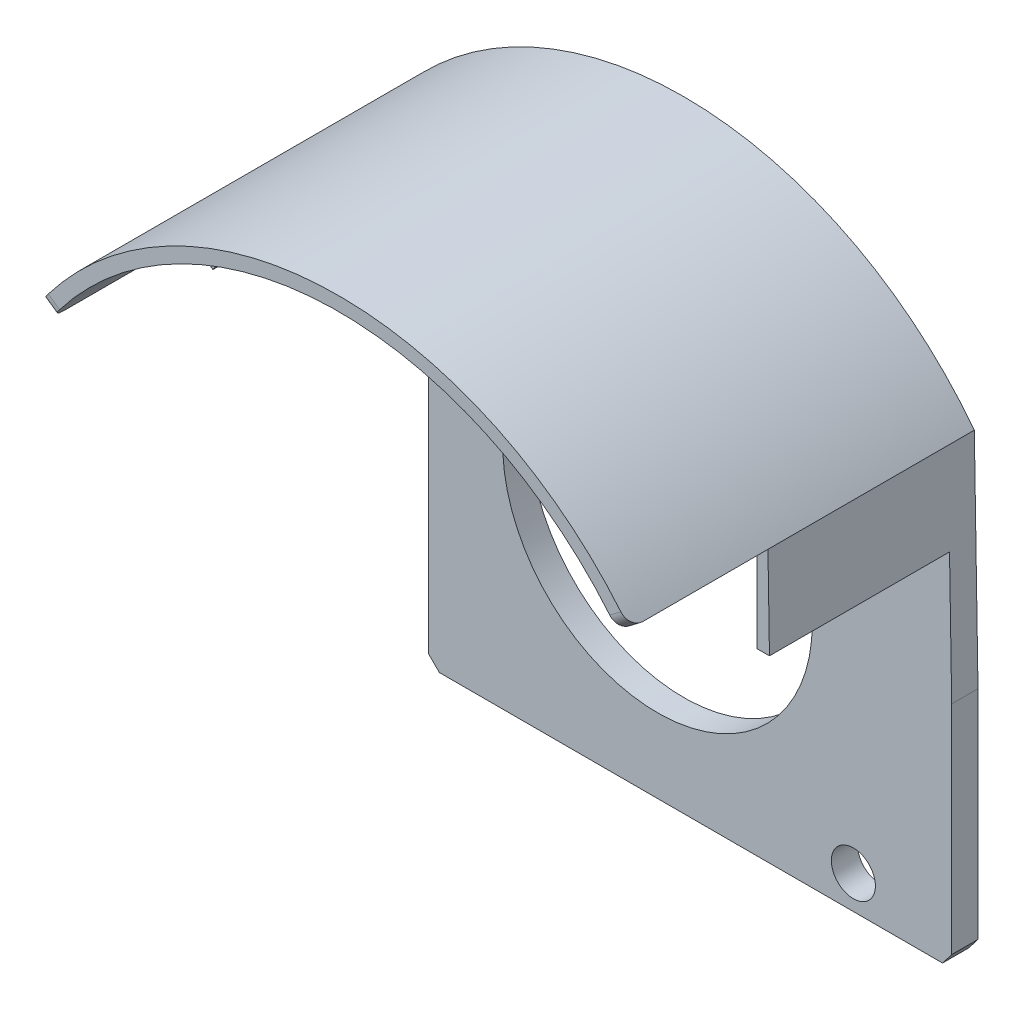
SolidWorks part; units mm, degrees
ref_plane "Front Plane" through (0, 0, 0) normal (0, 0, 1) x (1, 0, 0)
ref_plane "Top Plane" through (0, 0, 0) normal (0, 1, 0) x (1, 0, 0)
ref_plane "Right Plane" through (0, 0, 0) normal (1, 0, 0) x (0, 0, -1)
sketch "Sketch1" plane through (0, 0, 0) normal (0, 0, 1) x (1, 0, 0)
  line L1 (-21, 14.8277) -> (-21, -20)
  line L2 (-21, -20) -> (-20, -21)
  line L3 (-20, -21) -> (26.1367, -21)
  line L8 (28.2448, 0) -> (26.9748, 0) construction
  line L9 (28.2448, -18.7357) -> (28.2448, 18.7357) construction
  line L10 (26.9748, 0) -> (26.6379, 20.3604)
  line L12 (26.9748, 0) -> (26.9748, -19.912)
  line L13 (26.1367, -21) -> (26.9748, -19.912)
  line L14 (-21, 14.8277) -> (-27.3887, 19.3387)
  circle A0 centre (-17.9605, 17.9605) radius 2.0193
  circle A1 centre (17.9605, -17.9605) radius 2.0193
  circle A2 centre (0, 0) radius 14.195
  arc A6 (-27.3887, 19.3387) -> (26.6379, 20.3604) centre (0, 0) cw
extrude "Boss-Extrude1" add sketch "Sketch1" along normal blind 2.413
sketch "Sketch2" plane through (0, 0, 2.413) normal (0, 0, 1) x (1, 0, 0)
  line L0 (-26.3626, 18.5902) -> (-27.4004, 19.3221)
  line L1 (25.6289, 19.5892) -> (26.6379, 20.3604)
  arc A0 (26.6379, 20.3604) -> (-27.4004, 19.3221) centre (0, 0) ccw
  arc A1 (25.6289, 19.5892) -> (-26.3626, 18.5902) centre (0, 0) ccw
  dimension "D1" = 1.27
extrude "Boss-Extrude2" add sketch "Sketch2" along normal blind 29.21
sketch "Sketch3" plane through (0, 0, 2.413) normal (0, 0, 1) x (1, 0, 0)
  line L0 (25.6289, 19.5892) -> (25.6289, 11.9692)
  line L1 (25.6289, 11.9692) -> (26.7768, 11.9692)
  line L2 (26.9748, 0) -> (26.6379, 20.3604) construction
  line L3 (26.7768, 11.9692) -> (26.6379, 20.3604)
  line L4 (25.6289, 19.5892) -> (26.6379, 20.3604) construction
  line L5 (26.6379, 20.3604) -> (25.6289, 19.5892)
  line L7 (-25.5985, 19.629) -> (-23.5528, 18.1234)
  line L8 (-23.5528, 18.1234) -> (-24.2564, 17.127)
  line L9 (-26.3513, 18.6061) -> (-21, 14.8277) construction
  line L10 (-24.2564, 17.127) -> (-26.3513, 18.6061)
  line L12 (0.025, 32.258) -> (0.025, 25.908)
  line L13 (0.025, 25.908) -> (-1.245, 25.908)
  line L14 (-1.245, 25.908) -> (-1.245, 32.234)
  arc A0 (25.6289, 19.5892) -> (-26.3513, 18.6061) centre (0, 0) ccw construction
  arc A1 (0.025, 32.258) -> (-1.245, 32.234) centre (0, 0) ccw
  arc A2 (-25.5985, 19.629) -> (-26.3513, 18.6061) centre (0, 0) ccw
  arc M5 (25.6289, 19.5892) -> (-26.3513, 18.6061) centre (0, 0) ccw
  line M6 (-26.3513, 18.6061) -> (-21, 14.8277)
extrude "Boss-Extrude9" add sketch "Sketch3" along normal blind 16.51 contours L8 L7 M5 M6 | L14 A1 L12 L13 | L0 L1 L3 L5
fillet "Fillet1" radius 1.27 3 edges at (-26.8815, 18.9561, 31.623) (26.1334, 19.9748, 31.623) (-24.1944, 17.0832, 0)
